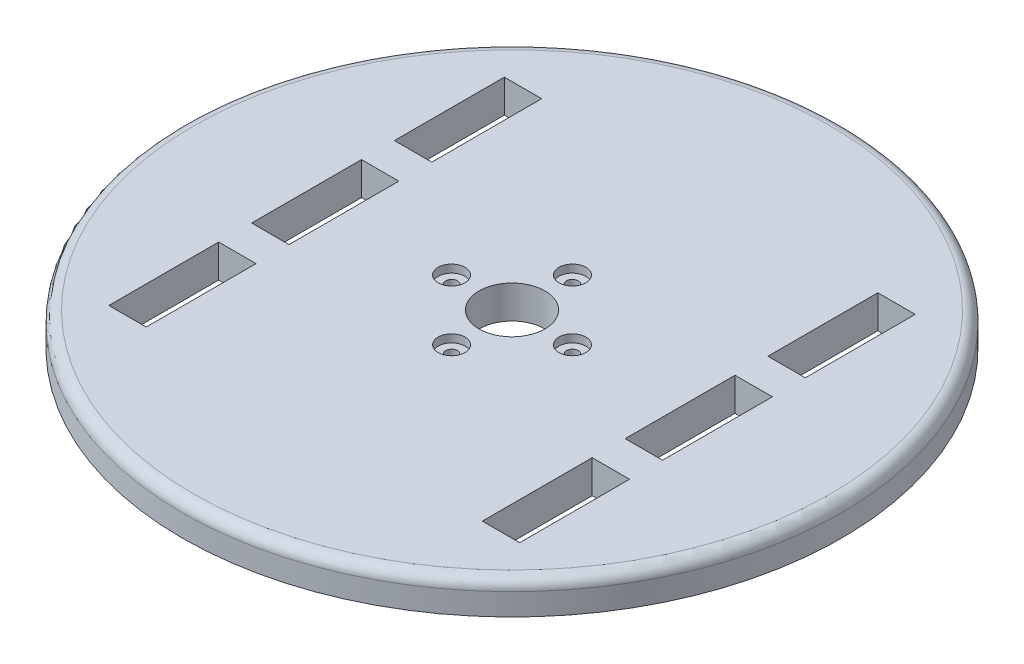
SolidWorks part; units mm, degrees
ref_plane "Front Plane" through (0, 0, 0) normal (0, 0, 1) x (1, 0, 0)
ref_plane "Top Plane" through (0, 0, 0) normal (0, 1, 0) x (1, 0, 0)
ref_plane "Right Plane" through (0, 0, 0) normal (1, 0, 0) x (0, 0, -1)
sketch "Sketch1" plane through (0, 0, 0) normal (0, 1, 0) x (1, 0, 0)
  circle A0 centre (0, 0) radius 150
  circle A1 centre (0, 0) radius 15
  dimension "D1" = 300
  dimension "D2" = 30
extrude "Boss-Extrude1" add sketch "Sketch1" along normal blind 15
sketch "Sketch2" plane through (0, 15, 0) normal (0, 1, 0) x (1, 0, 0)
  line L0 (0, 0) -> (0, 27.5) construction
  circle A0 centre (0, 0) radius 27.5
  dimension "D1" = 55
hole_wizard "CBORE for M5 Hex Head Bolt1" positions "3DSketch2" profile "Sketch4" counterbore size "M5" standard "ANSI Metric" end condition through all
sketch3d "3DSketch2"
  point P0 (0, 15, -27.5)
sketch "Sketch4" plane through (0, 15, -27.5) normal (1, 0, 0) x (0, 0, 1)
  line L0 (0, 0) -> (0, 15)
  line L1 (0, 15) -> (2.65, 15)
  line L3 (2.65, 15) -> (2.65, 3.58)
  line L4 (2.65, 3.58) -> (6.12, 3.58)
  line L5 (6.12, 3.58) -> (6.12, 0)
  line L7 (6.12, 0) -> (0, 0)
  line L11 (0, -6.35) -> (0, 107.95) construction
  dimension "Thru Hole Dia." = 5.3
  dimension "Thru Hole Depth" = 15
  dimension "C'Bore Dia." = 12.24
  dimension "C'Bore Depth" = 3.58
pattern_circular "CirPattern1" count 4 over 360 about axis through (0, 0, 0) along (0, 1, 0) of "CBORE for M5 Hex Head Bolt1"
sketch "Sketch5" plane through (0, 0, 0) normal (0, -1, 0) x (1, 0, 0)
  line L0 (-150, 0) -> (150, 0) construction
  line L1 (0, 150) -> (0, -150) construction
  line L2 (-76.5, 40) -> (-76.5, 90)
  line L3 (-76.5, -25) -> (-93.5, -25)
  line L4 (-76.5, -25) -> (-76.5, 25)
  line L5 (-76.5, 25) -> (-93.5, 25)
  line L6 (-93.5, -25) -> (-93.5, 25)
  line L7 (-85, 25) -> (-85, -25) construction
  line L8 (-76.5, 0) -> (-93.5, 0) construction
  line L9 (-76.5, 90) -> (-93.5, 90)
  line L10 (-93.5, 40) -> (-93.5, 90)
  line L11 (-76.5, 40) -> (-93.5, 40)
  line L12 (-93.5, -90) -> (-93.5, -40)
  line L13 (-76.5, -90) -> (-76.5, -40)
  line L14 (-76.5, -40) -> (-93.5, -40)
  line L15 (-76.5, -90) -> (-93.5, -90)
  line L16 (93.5, 90) -> (76.5, 90)
  line L17 (76.5, 40) -> (76.5, 90)
  line L18 (93.5, 40) -> (93.5, 90)
  line L19 (93.5, 40) -> (76.5, 40)
  line L20 (76.5, -25) -> (76.5, 25)
  line L21 (93.5, 25) -> (76.5, 25)
  line L22 (93.5, -25) -> (93.5, 25)
  line L23 (93.5, -25) -> (76.5, -25)
  line L24 (76.5, -90) -> (76.5, -40)
  line L25 (93.5, -40) -> (76.5, -40)
  line L26 (93.5, -90) -> (93.5, -40)
  line L27 (93.5, -90) -> (76.5, -90)
  line L28 (-76.5, 90) -> (93.5, 90) construction
  circle A0 centre (0, 0) radius 150 construction
  circle A2 centre (0, 0) radius 15 construction
  point P7 (-85, 0)
  point P15 (-85, -40)
  dimension "D1" = 85
  dimension "D2" = 17
  dimension "D3" = 50
  dimension "D5" = 15
  dimension "D7" = 15
  dimension "D8" = 2
  dimension "D9" = 170
  dimension "D4" = 2
  dimension "D6" = 2
extrude "Cut-Extrude1" cut sketch "Sketch5" against normal through all
fillet "Fillet1" radius 5 1 edges at (0, 15, 150)
